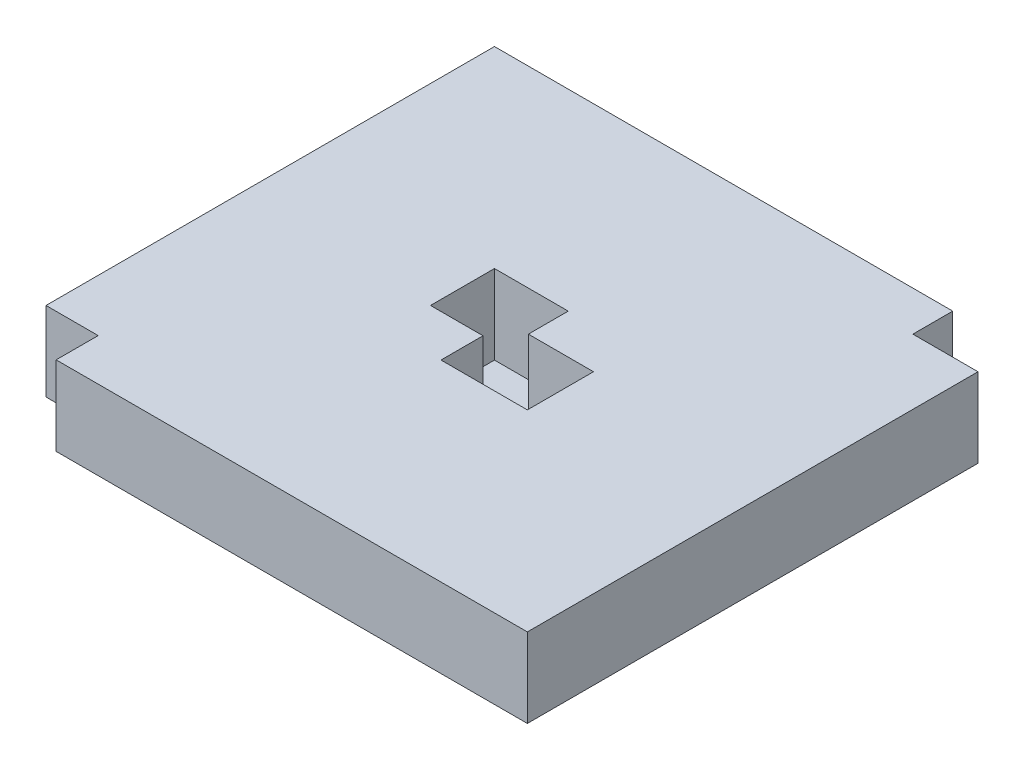
SolidWorks part; units mm, degrees
ref_plane "Ebene vorne" through (0, 0, 0) normal (0, 0, 1) x (1, 0, 0)
ref_plane "Ebene oben" through (0, 0, 0) normal (0, 1, 0) x (1, 0, 0)
ref_plane "Ebene rechts" through (0, 0, 0) normal (1, 0, 0) x (0, 0, -1)
sketch "Skizze1" plane through (0, 0, 0) normal (0, 1, 0) x (1, 0, 0)
  circle A0 centre (0, 0) radius 49.5719
extrude "Aufsatz-Linear austragen6" add sketch "Skizze1" along normal blind 33
sketch "Skizze2" plane through (0, 33, 0) normal (0, 1, 0) x (1, 0, 0)
  line L1 (-30.6943, 26.6156) -> (0, 26.6156)
  line L2 (-30.6943, 26.6156) -> (-30.6943, 0)
  line L3 (-30.6943, 0) -> (-8.8488, 0)
  line L4 (0, 26.6156) -> (0, 10.3006)
  line L5 (0, 10.024) -> (27.0995, 10.024)
  line L6 (-8.9871, 0) -> (-8.9871, -17.4902)
  line L7 (-8.9871, -17.4902) -> (27.0995, -17.4902)
  line L8 (27.0995, 10.024) -> (27.0995, -17.4902)
  point P1 (0, 0)
extrude "Linear-Austragen-Dünn9" add sketch "Skizze2" along normal blind 33 thin thin type one direction wall 80
